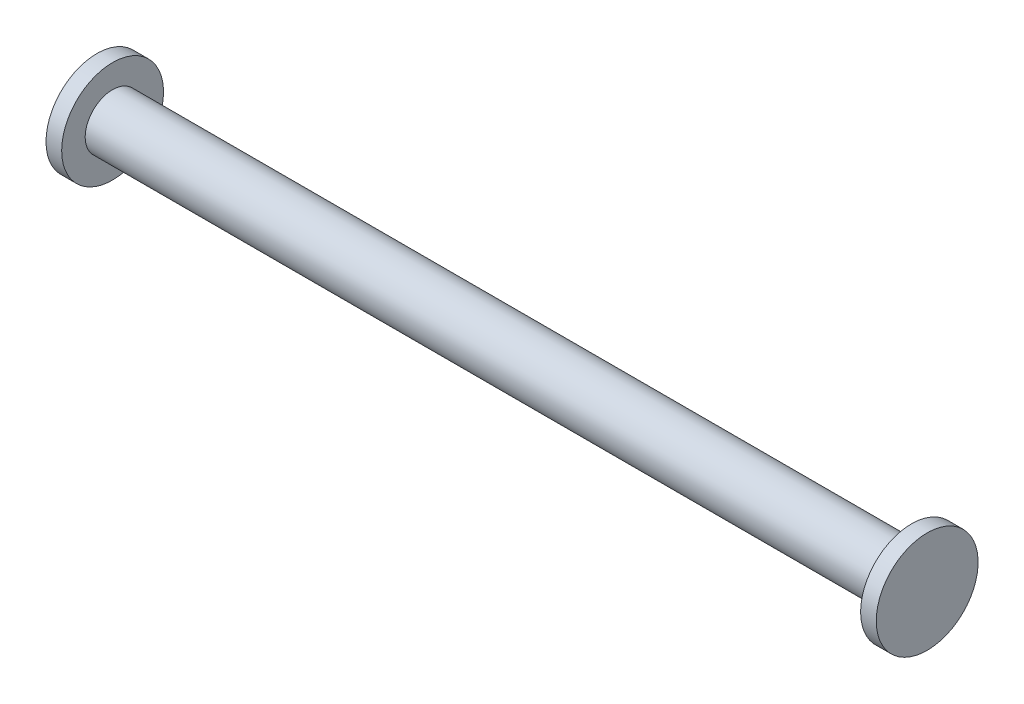
SolidWorks part; units mm, degrees
ref_plane "Front Plane" through (0, 0, 0) normal (0, 0, 1) x (1, 0, 0)
ref_plane "Top Plane" through (0, 0, 0) normal (0, 1, 0) x (1, 0, 0)
ref_plane "Right Plane" through (0, 0, 0) normal (1, 0, 0) x (0, 0, -1)
sketch "Sketch1" plane through (0, 0, 0) normal (0, 1, 0) x (1, 0, 0)
  line L0 (-53, 0) -> (53, 0) construction
  line L1 (53, 0) -> (53, 6.5)
  line L2 (53, 6.5) -> (51, 6.5)
  line L3 (51, 6.5) -> (51, 3.5)
  line L4 (51, 3.5) -> (-51, 3.5)
  line L5 (-51, 3.5) -> (-51, 6.5)
  line L6 (-51, 6.5) -> (-53, 6.5)
  line L7 (-53, 6.5) -> (-53, 0)
  line L9 (53, 0) -> (-53, 0)
  point P0 (0, 0)
  dimension "D1" = 6.5
  dimension "D2" = 3
  dimension "D3" = 106
  dimension "D4" = 2
revolve "Revolve1" add sketch "Sketch1" angle 360 about L0
